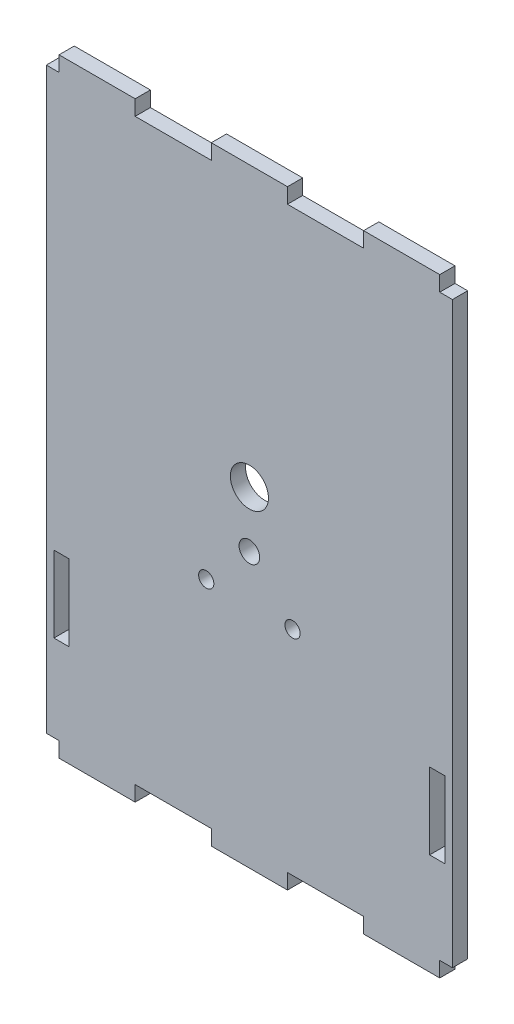
SolidWorks part; units mm, degrees
ref_plane "前视基准面" through (0, 0, 0) normal (0, 0, 1) x (1, 0, 0)
ref_plane "上视基准面" through (0, 0, 0) normal (0, 1, 0) x (1, 0, 0)
ref_plane "右视基准面" through (0, 0, 0) normal (1, 0, 0) x (0, 0, -1)
other "Configuration Table"
sketch "草图1" plane through (0, 0, 0) normal (0, 0, 1) x (1, 0, 0)
  line L0 (2.5, 3) -> (0, 3)
  line L2 (0, 3) -> (0, 117)
  line L4 (80, 3) -> (80, 117)
  line L5 (2.5, 0) -> (17.5, 0)
  line L6 (2.5, 0) -> (2.5, 3)
  line L8 (17.5, 0) -> (17.5, 3)
  line L9 (17.5, 3) -> (32.5, 3)
  line L10 (32.5, 0) -> (47.5, 0)
  line L11 (32.5, 0) -> (32.5, 3)
  line L13 (47.5, 0) -> (47.5, 3)
  line L14 (62.5, 0) -> (77.5, 0)
  line L15 (62.5, 0) -> (62.5, 3)
  line L17 (77.5, 0) -> (77.5, 3)
  line L18 (47.5, 3) -> (62.5, 3)
  line L19 (77.5, 3) -> (80, 3)
  line L20 (0, 120) -> (80, 0) construction
  line L21 (78.5, 20) -> (75.5, 20)
  line L22 (78.5, 20) -> (78.5, 35)
  line L23 (78.5, 35) -> (75.5, 35)
  line L24 (75.5, 20) -> (75.5, 35)
  line L25 (1.5, 20) -> (1.5, 35)
  line L26 (1.5, 35) -> (4.5, 35)
  line L27 (4.5, 20) -> (4.5, 35)
  line L28 (1.5, 20) -> (4.5, 20)
  line L29 (-20.6033, 60) -> (100.6033, 60) construction
  line L30 (77.5, 117) -> (80, 117)
  line L31 (77.5, 120) -> (77.5, 117)
  line L32 (77.5, 120) -> (62.5, 120)
  line L33 (62.5, 120) -> (62.5, 117)
  line L34 (47.5, 117) -> (62.5, 117)
  line L35 (47.5, 120) -> (47.5, 117)
  line L36 (2.5, 120) -> (17.5, 120)
  line L37 (32.5, 120) -> (32.5, 117)
  line L38 (17.5, 117) -> (32.5, 117)
  line L39 (2.5, 120) -> (2.5, 117)
  line L40 (17.5, 120) -> (17.5, 117)
  line L41 (32.5, 120) -> (47.5, 120)
  line L42 (2.5, 117) -> (0, 117)
  point P4 (80, 0)
  point P13 (17.5, 1.5)
  point P19 (62.5, 1.5)
  point P24 (0, 120)
  point P32 (40, 60)
  dimension "D3" = 15
  dimension "D4" = 3
  dimension "D5" = 2.5
  dimension "D6" = 15
  dimension "D7" = 15
  dimension "D8" = 3
  dimension "D9" = 15
  dimension "D10" = 1.5
  dimension "D11" = 20
  dimension "D12" = 20
  dimension "D13" = 1.5
  dimension "D14" = 3
extrude "凸台-拉伸1" add sketch "草图1" along normal blind 3
sketch "草图2" plane through (0, 0, 3) normal (0, 0, 1) x (1, 0, 0)
  line L0 (80, 3) -> (80, 117) construction
  line L1 (62.5, 0) -> (77.5, 0) construction
  line L2 (0, 117) -> (0, 3) construction
  line L4 (17.5, 120) -> (2.5, 120) construction
  line L5 (0, 120) -> (80, 0) construction
  line L6 (-9.3374, 60) -> (89.3374, 60) construction
  line L7 (-9.3374, 45) -> (89.3374, 45) construction
  line L8 (40, 60) -> (40, -2.9674) construction
  line L9 (32.5, 0) -> (47.5, 0) construction
  circle A0 centre (31.5, 45) radius 1.5
  circle A1 centre (48.5, 45) radius 1.5
  circle A2 centre (40, 54) radius 2.03
  circle A3 centre (40, 65) radius 3.75
  point P0 (80, 0)
  point P5 (0, 120)
  point P15 (40, 60)
  point P18 (40, 45)
  point P28 (40, 66.4776)
  dimension "D2" = 3
  dimension "D4" = 4.06
  dimension "D6" = 7.5
  dimension "D1" = 15
  dimension "D3" = 17
  dimension "D5" = 9
  dimension "D7" = 20
extrude "切除-拉伸1" cut sketch "草图2" against normal blind 10
